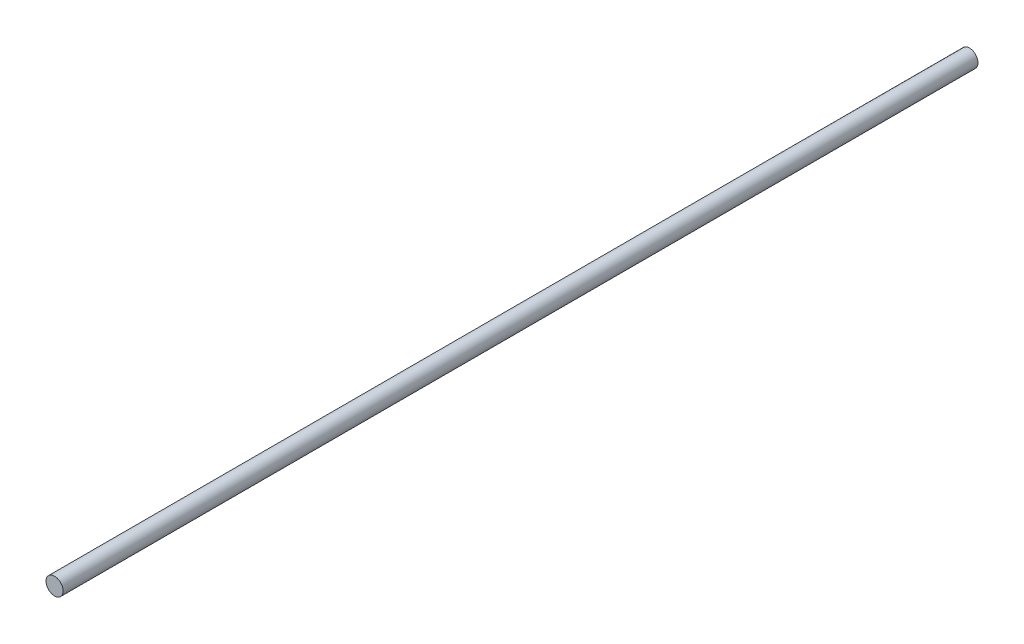
SolidWorks part; units mm, degrees
ref_plane "Front Plane" through (0, 0, 0) normal (0, 0, 1) x (1, 0, 0)
ref_plane "Top Plane" through (0, 0, 0) normal (0, 1, 0) x (1, 0, 0)
ref_plane "Right Plane" through (0, 0, 0) normal (1, 0, 0) x (0, 0, -1)
sketch "Sketch1" plane through (0, 0, 0) normal (0, 0, 1) x (1, 0, 0)
  circle A0 centre (0, 0) radius 1.5
  dimension "D1" = 3
extrude "Boss-Extrude1" add sketch "Sketch1" along normal blind 160
